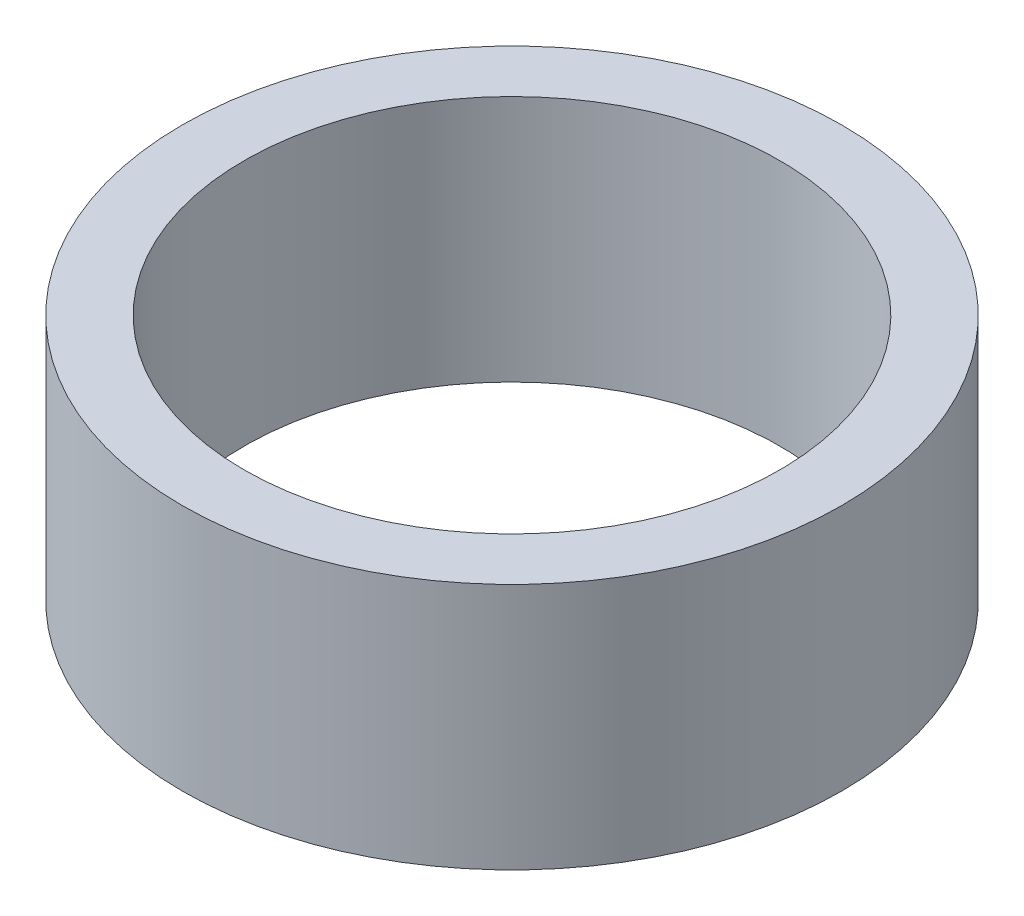
SolidWorks part; units mm, degrees
ref_plane "Спереди" through (0, 0, 0) normal (0, 0, 1) x (1, 0, 0)
ref_plane "Сверху" through (0, 0, 0) normal (0, 1, 0) x (1, 0, 0)
ref_plane "Справа" through (0, 0, 0) normal (1, 0, 0) x (0, 0, -1)
sketch "Эскиз1" plane through (0, 0, 0) normal (0, 1, 0) x (1, 0, 0)
  circle A0 centre (0, 0) radius 3.25
  circle A1 centre (0, 0) radius 4
  dimension "D1" = 6.5
  dimension "D2" = 8
extrude "Бобышка-Вытянуть1" add sketch "Эскиз1" along normal blind 3
